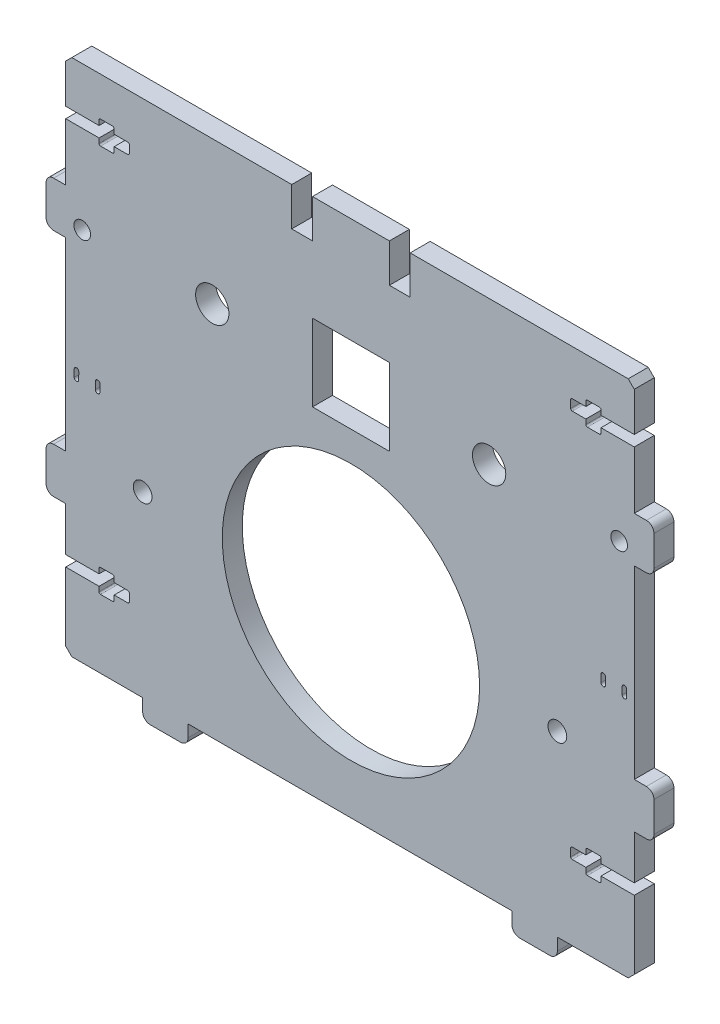
SolidWorks part; units mm, degrees
ref_plane "Front Plane" through (0, 0, 0) normal (0, 0, 1) x (1, 0, 0)
ref_plane "Top Plane" through (0, 0, 0) normal (0, 1, 0) x (1, 0, 0)
ref_plane "Right Plane" through (0, 0, 0) normal (1, 0, 0) x (0, 0, -1)
sketch "Model" plane through (0, 0, 0) normal (0, 0, 1) x (1, 0, 0)
  line L0 (187.8, 2) -> (187.8, 24.665)
  line L1 (185.8, 0) -> (187.8, 2)
  line L2 (162.4, 0) -> (185.8, 0)
  line L3 (162.4, -4) -> (162.4, 0)
  line L4 (149.9, -6.5) -> (159.9, -6.5)
  line L5 (147.4, 0) -> (147.4, -4)
  line L6 (40.4, 0) -> (147.4, 0)
  line L7 (27.9, -6.5) -> (37.9, -6.5)
  line L8 (25.4, 0) -> (25.4, -4)
  line L9 (2, 0) -> (25.4, 0)
  line L10 (0, 2) -> (2, 0)
  line L11 (0, 24.665) -> (0, 2)
  line L12 (0, 24.665) -> (11, 24.665)
  line L13 (11, 24.665) -> (11, 23.08)
  line L14 (11.5, 22.58) -> (15.5, 22.58)
  line L15 (16, 23.08) -> (16, 24.665)
  line L16 (16, 24.665) -> (20.5, 24.665)
  line L17 (21, 25.165) -> (21, 27.715)
  line L18 (20.5, 28.215) -> (16, 28.215)
  line L19 (16, 28.215) -> (16, 29.8)
  line L20 (15.5, 30.3) -> (11.5, 30.3)
  line L21 (11, 29.8) -> (11, 28.215)
  line L22 (11, 28.215) -> (0, 28.215)
  line L23 (0, 42.8) -> (0, 28.215)
  line L24 (-4, 42.8) -> (0, 42.8)
  line L25 (-6.5, 55.3) -> (-6.5, 45.3)
  line L26 (0, 57.8) -> (-4, 57.8)
  line L27 (0, 118.92) -> (0, 57.8)
  line L28 (-4, 118.92) -> (0, 118.92)
  line L29 (-6.5, 131.42) -> (-6.5, 121.42)
  line L30 (0, 133.92) -> (-4, 133.92)
  line L31 (0, 152.92) -> (0, 133.92)
  line L32 (0, 152.92) -> (11, 152.92)
  line L33 (11, 152.92) -> (11, 151.335)
  line L34 (11.5, 150.835) -> (15.5, 150.835)
  line L35 (16, 151.335) -> (16, 152.92)
  line L36 (16, 152.92) -> (20.5, 152.92)
  line L37 (21, 153.42) -> (21, 155.97)
  line L38 (20.5, 156.47) -> (16, 156.47)
  line L39 (16, 156.47) -> (16, 158.055)
  line L40 (15.5, 158.555) -> (11.5, 158.555)
  line L41 (11, 158.055) -> (11, 156.47)
  line L42 (11, 156.47) -> (0, 156.47)
  line L43 (0, 169.42) -> (0, 156.47)
  line L44 (2, 171.42) -> (0, 169.42)
  line L45 (74.65, 171.42) -> (2, 171.42)
  line L46 (74.65, 171.42) -> (74.65, 158.72)
  line L47 (74.65, 158.72) -> (81.51, 158.72)
  line L48 (81.51, 158.72) -> (81.51, 171.42)
  line L49 (106.91, 171.42) -> (81.51, 171.42)
  line L50 (106.91, 171.42) -> (106.91, 158.72)
  line L51 (106.91, 158.72) -> (113.77, 158.72)
  line L52 (113.77, 158.72) -> (113.77, 171.42)
  line L53 (185.8, 171.42) -> (113.77, 171.42)
  line L54 (187.8, 169.42) -> (185.8, 171.42)
  line L55 (187.8, 156.47) -> (187.8, 169.42)
  line L56 (187.8, 156.47) -> (176.8, 156.47)
  line L57 (176.8, 156.47) -> (176.8, 158.055)
  line L58 (176.3, 158.555) -> (172.3, 158.555)
  line L59 (171.8, 158.055) -> (171.8, 156.47)
  line L60 (171.8, 156.47) -> (167.3, 156.47)
  line L61 (166.8, 155.97) -> (166.8, 153.42)
  line L62 (167.3, 152.92) -> (171.8, 152.92)
  line L63 (171.8, 152.92) -> (171.8, 151.335)
  line L64 (172.3, 150.835) -> (176.3, 150.835)
  line L65 (176.8, 151.335) -> (176.8, 152.92)
  line L66 (176.8, 152.92) -> (187.8, 152.92)
  line L67 (187.8, 133.92) -> (187.8, 152.92)
  line L68 (191.8, 133.92) -> (187.8, 133.92)
  line L69 (194.3, 121.42) -> (194.3, 131.42)
  line L70 (187.8, 118.92) -> (191.8, 118.92)
  line L71 (187.8, 57.8) -> (187.8, 118.92)
  line L72 (191.8, 57.8) -> (187.8, 57.8)
  line L73 (194.3, 45.3) -> (194.3, 55.3)
  line L74 (187.8, 42.8) -> (191.8, 42.8)
  line L75 (187.8, 28.215) -> (187.8, 42.8)
  line L76 (187.8, 28.215) -> (176.8, 28.215)
  line L77 (176.8, 28.215) -> (176.8, 29.8)
  line L78 (176.3, 30.3) -> (172.3, 30.3)
  line L79 (171.8, 29.8) -> (171.8, 28.215)
  line L80 (171.8, 28.215) -> (167.3, 28.215)
  line L81 (166.8, 27.715) -> (166.8, 25.165)
  line L82 (167.3, 24.665) -> (171.8, 24.665)
  line L83 (171.8, 24.665) -> (171.8, 23.08)
  line L84 (172.3, 22.58) -> (176.3, 22.58)
  line L85 (176.8, 23.08) -> (176.8, 24.665)
  line L86 (176.8, 24.665) -> (187.8, 24.665)
  line L87 (106.91, 111.2248) -> (106.91, 136.6248)
  line L88 (106.91, 136.6248) -> (81.51, 136.6248)
  line L89 (81.51, 136.6248) -> (81.51, 111.2248)
  line L90 (81.51, 111.2248) -> (106.91, 111.2248)
  line L91 (183.8, 82.4) -> (183.8, 80)
  line L92 (185.3, 80) -> (185.3, 82.4)
  line L93 (176.8, 82.4) -> (176.8, 80)
  line L94 (178.3, 80) -> (178.3, 82.4)
  line L95 (9.7986, 82.7047) -> (9.7899, 80.3047)
  line L96 (11.2899, 80.2993) -> (11.2986, 82.6993)
  line L97 (2.7986, 82.73) -> (2.7899, 80.3301)
  line L98 (4.2899, 80.3246) -> (4.2986, 82.7246)
  line L99 (40.4, -4) -> (40.4, 0)
  circle A0 centre (94.21, 58.8721) radius 42.5
  circle A1 centre (139.852, 123.9248) radius 5.5
  circle A2 centre (48.3965, 124.0902) radius 5.5
  circle A3 centre (182.8, 123.5) radius 2.75
  circle A4 centre (5.4473, 123.8207) radius 2.75
  circle A5 centre (162.4, 58.8721) radius 3.1
  circle A6 centre (25.4, 58.8721) radius 3.1
  arc A7 (159.9, -6.5) -> (162.4, -4) centre (159.9, -4) ccw
  arc A8 (147.4, -4) -> (149.9, -6.5) centre (149.9, -4) ccw
  arc A9 (37.9, -6.5) -> (40.4, -4) centre (37.9, -4) ccw
  arc A10 (25.4, -4) -> (27.9, -6.5) centre (27.9, -4) ccw
  arc A11 (11, 23.08) -> (11.5, 22.58) centre (11.5, 23.08) ccw
  arc A12 (15.5, 22.58) -> (16, 23.08) centre (15.5, 23.08) ccw
  arc A13 (20.5, 24.665) -> (21, 25.165) centre (20.5, 25.165) ccw
  arc A14 (21, 27.715) -> (20.5, 28.215) centre (20.5, 27.715) ccw
  arc A15 (16, 29.8) -> (15.5, 30.3) centre (15.5, 29.8) ccw
  arc A16 (11.5, 30.3) -> (11, 29.8) centre (11.5, 29.8) ccw
  arc A17 (-6.5, 45.3) -> (-4, 42.8) centre (-4, 45.3) ccw
  arc A18 (-4, 57.8) -> (-6.5, 55.3) centre (-4, 55.3) ccw
  arc A19 (-6.5, 121.42) -> (-4, 118.92) centre (-4, 121.42) ccw
  arc A20 (-4, 133.92) -> (-6.5, 131.42) centre (-4, 131.42) ccw
  arc A21 (11, 151.335) -> (11.5, 150.835) centre (11.5, 151.335) ccw
  arc A22 (15.5, 150.835) -> (16, 151.335) centre (15.5, 151.335) ccw
  arc A23 (20.5, 152.92) -> (21, 153.42) centre (20.5, 153.42) ccw
  arc A24 (21, 155.97) -> (20.5, 156.47) centre (20.5, 155.97) ccw
  arc A25 (16, 158.055) -> (15.5, 158.555) centre (15.5, 158.055) ccw
  arc A26 (11.5, 158.555) -> (11, 158.055) centre (11.5, 158.055) ccw
  arc A27 (176.8, 158.055) -> (176.3, 158.555) centre (176.3, 158.055) ccw
  arc A28 (172.3, 158.555) -> (171.8, 158.055) centre (172.3, 158.055) ccw
  arc A29 (167.3, 156.47) -> (166.8, 155.97) centre (167.3, 155.97) ccw
  arc A30 (166.8, 153.42) -> (167.3, 152.92) centre (167.3, 153.42) ccw
  arc A31 (171.8, 151.335) -> (172.3, 150.835) centre (172.3, 151.335) ccw
  arc A32 (176.3, 150.835) -> (176.8, 151.335) centre (176.3, 151.335) ccw
  arc A33 (194.3, 131.42) -> (191.8, 133.92) centre (191.8, 131.42) ccw
  arc A34 (191.8, 118.92) -> (194.3, 121.42) centre (191.8, 121.42) ccw
  arc A35 (194.3, 55.3) -> (191.8, 57.8) centre (191.8, 55.3) ccw
  arc A36 (191.8, 42.8) -> (194.3, 45.3) centre (191.8, 45.3) ccw
  arc A37 (176.8, 29.8) -> (176.3, 30.3) centre (176.3, 29.8) ccw
  arc A38 (172.3, 30.3) -> (171.8, 29.8) centre (172.3, 29.8) ccw
  arc A39 (167.3, 28.215) -> (166.8, 27.715) centre (167.3, 27.715) ccw
  arc A40 (166.8, 25.165) -> (167.3, 24.665) centre (167.3, 25.165) ccw
  arc A41 (171.8, 23.08) -> (172.3, 22.58) centre (172.3, 23.08) ccw
  arc A42 (176.3, 22.58) -> (176.8, 23.08) centre (176.3, 23.08) ccw
  arc A43 (185.3, 82.4) -> (183.8, 82.4) centre (184.55, 82.4) ccw
  arc A44 (183.8, 80) -> (185.3, 80) centre (184.55, 80) ccw
  arc A45 (178.3, 82.4) -> (176.8, 82.4) centre (177.55, 82.4) ccw
  arc A46 (176.8, 80) -> (178.3, 80) centre (177.55, 80) ccw
  arc A47 (11.2986, 82.6993) -> (9.7986, 82.7047) centre (10.5486, 82.702) ccw
  arc A48 (9.7899, 80.3047) -> (11.2899, 80.2993) centre (10.5399, 80.302) ccw
  arc A49 (4.2986, 82.7246) -> (2.7986, 82.73) centre (3.5486, 82.7273) ccw
  arc A50 (2.7899, 80.3301) -> (4.2899, 80.3246) centre (3.5399, 80.3273) ccw
extrude "Boss-Extrude1" add sketch "Model" along normal blind 6.6
